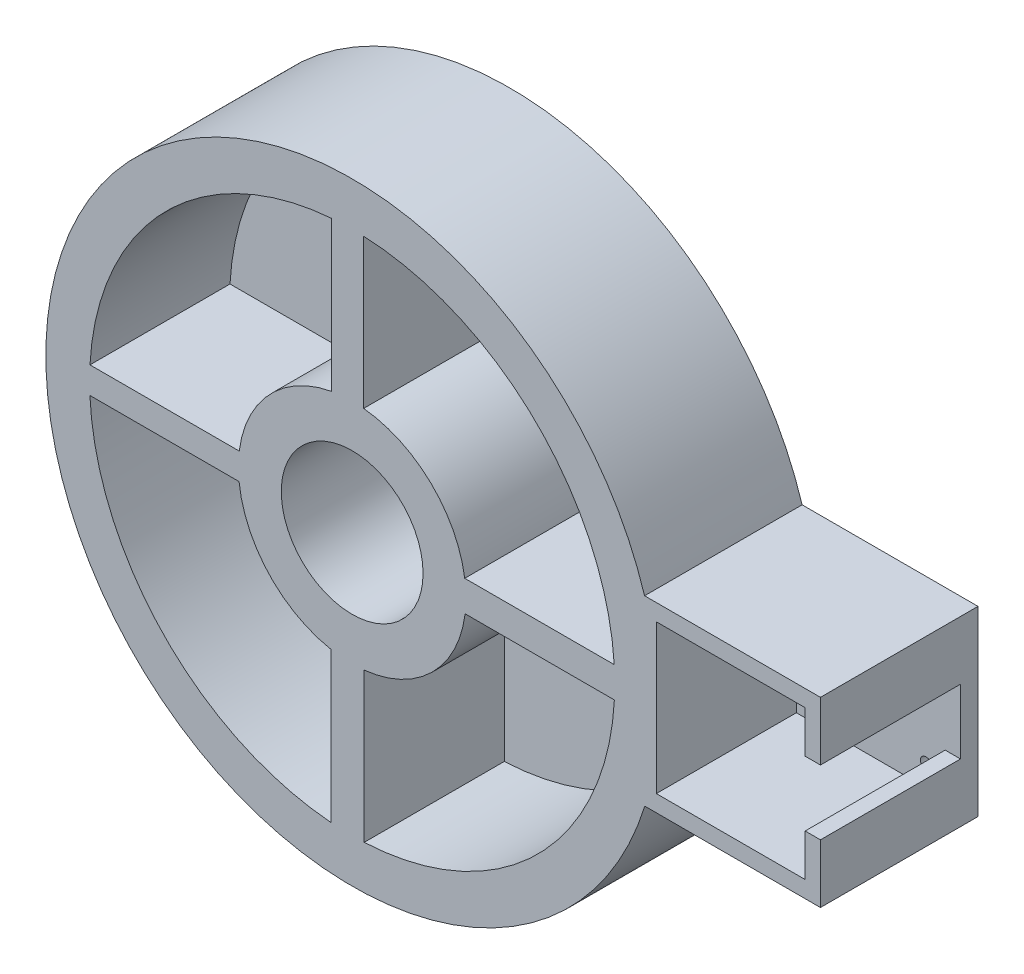
SolidWorks part; units mm, degrees
ref_plane "Front Plane" through (0, 0, 0) normal (1, 0, 0) x (0, 1, 0)
ref_plane "Top Plane" through (0, 0, 0) normal (0, 0, 1) x (0, 1, 0)
ref_plane "Right Plane" through (0, 0, 0) normal (0, 1, 0) x (-1, 0, 0)
sketch "Sketch1" plane through (0, 0, 0) normal (0, 0, 1) x (0, 1, 0)
  line L0 (74.7541, 18.7511) -> (74.7541, -170.9285) construction
  line L5 (-17.0261, -75) -> (164.516, -75) construction
  line L6 (149.5245, -70.2254) -> (106.7208, -70.2254)
  line L7 (149.6823, -79.3694) -> (107.0881, -79.3694)
  line L8 (70.7832, -150.9835) -> (70.7832, -108.3452)
  line L9 (79.4985, -150.9385) -> (79.4985, -108.2405)
  line L10 (-0.0039, -70.0678) -> (42.8166, -70.0678)
  line L11 (-0.1671, -79.527) -> (42.4365, -79.527)
  line L12 (71.2039, -1.1727) -> (71.2039, -43.7831)
  line L13 (78.7713, -1.1963) -> (78.7713, -43.8379)
  line L14 (48.8611, -159.6698) -> (48.8611, -209.836)
  line L15 (53.8611, -163.5887) -> (95.8611, -163.5887)
  line L16 (53.8611, -163.5887) -> (53.8611, -204.836)
  line L17 (53.8611, -204.836) -> (65.8611, -204.836)
  line L18 (95.8611, -163.5887) -> (95.8611, -204.836)
  line L19 (48.8611, -209.836) -> (65.8611, -209.836)
  line L20 (100.8611, -159.6032) -> (100.8611, -209.836)
  line L22 (83.8611, -209.836) -> (100.8611, -209.836)
  line L23 (48.8611, -158.5887) -> (100.8611, -158.5887) construction
  line L24 (48.8611, -158.5887) -> (48.8611, -209.836) construction
  line L25 (100.8611, -158.5887) -> (100.8611, -209.836) construction
  line L26 (65.8611, -204.836) -> (65.8611, -209.836)
  line L27 (83.8611, -204.836) -> (83.8611, -209.836)
  line L28 (83.8611, -204.836) -> (95.8611, -204.836)
  line L30 (53.8611, -204.836) -> (95.8611, -204.836) construction
  line L31 (48.8611, -209.836) -> (100.8611, -209.836) construction
  arc A0 (71.2039, -1.1727) -> (-0.0039, -70.0678) centre (74.7541, -76.0887) ccw
  arc A1 (100.8611, -159.6032) -> (48.8611, -159.6698) centre (74.7541, -76.0887) ccw
  circle A2 centre (74.7541, -76.0887) radius 20
  arc A3 (71.2039, -43.7831) -> (42.8166, -70.0678) centre (74.7541, -76.0887) ccw
  arc A4 (-0.1671, -79.527) -> (70.7832, -150.9835) centre (74.7541, -76.0887) ccw
  circle A5 centre (74.7541, -76.0887) radius 75 construction
  arc A6 (149.5245, -70.2254) -> (78.7713, -1.1963) centre (74.7541, -76.0887) ccw
  arc A7 (79.4985, -150.9385) -> (149.6823, -79.3694) centre (74.7541, -76.0887) ccw
  arc A8 (42.4365, -79.527) -> (70.7832, -108.3452) centre (74.7541, -76.0887) ccw
  circle A9 centre (74.7541, -76.0887) radius 32.5 construction
  arc A10 (79.4985, -108.2405) -> (107.0881, -79.3694) centre (74.7541, -76.0887) ccw
  arc A11 (106.7208, -70.2254) -> (78.7713, -43.8379) centre (74.7541, -76.0887) ccw
  circle A13 centre (74.7541, -76.0887) radius 87.5 construction
  point P3 (146.7229, -53.1149)
  point P13 (107.5, -75.0428)
  point P33 (158.4294, -49.4603)
  dimension "D1" = 150
  dimension "D2" = 40
  dimension "D4" = 12.5
  dimension "D5" = 5
  dimension "D6" = 42
  dimension "D3" = 12.5
extrude "Boss-Extrude4" add sketch "Sketch1" along normal blind 40 contours A2 | A3 L10 A0 L12 | A4 L8 A8 L11 | L6 A11 L13 A6 | A7 L7 A10 L9 | L14 L19 L26 L17 L16 L15 L18 L28 L27 L22 L20 A1
sketch "Sketch4" plane through (0, 0, 0) normal (0, 0, -1) x (1, 0, 0)
  line L0 (159.6698, -48.8611) -> (209.836, -48.8611)
  line L1 (159.6698, -48.8611) -> (209.836, -48.8611) construction
  line L2 (209.836, -48.8611) -> (209.836, -65.8611) construction
  line L3 (209.836, -48.8611) -> (209.836, -100.8611)
  line L4 (209.836, -100.8611) -> (159.6032, -100.8611)
  arc A0 (159.6698, -48.8611) -> (159.6032, -100.8611) centre (76.0887, -74.7541) ccw
extrude "Boss-Extrude5" add sketch "Sketch4" along normal blind 5
sketch "Sketch6" plane through (0, 0, -5) normal (0, 0, -1) x (1, 0, 0)
  circle A0 centre (199.9623, -59.6111) radius 1.25
  circle A1 centre (168.9623, -59.6111) radius 1.25
  circle A2 centre (168.9623, -90.6111) radius 1.25
  circle A3 centre (199.9623, -90.6111) radius 1.25
extrude "Cut-Extrude1" cut sketch "Sketch6" against normal blind 5
sketch "Sketch7" plane through (0, 0, -5) normal (0, 0, -1) x (-1, 0, 0)
  circle A0 centre (-199.9623, 59.6111) radius 3
  circle A1 centre (-168.9623, 59.6111) radius 3
  circle A2 centre (-168.9623, 90.6111) radius 3
  circle A3 centre (-199.9623, 90.6111) radius 3
extrude "Cut-Extrude2" cut sketch "Sketch7" against normal blind 2
sketch "Sketch8" plane through (0, 0, 40) normal (0, 0, 1) x (1, 0, 0)
  circle A0 centre (76.0887, 74.7541) radius 20.25
  dimension "D1" = 40.5
extrude "Cut-Extrude3" cut sketch "Sketch8" against normal blind 40
sketch "Sketch9" plane through (0, 0, 40) normal (0, 0, 1) x (1, 0, 0)
  line L0 (163.5887, 53.8611) -> (204.836, 95.8611) construction
  line L1 (163.5887, 95.8611) -> (204.836, 53.8611) construction
  line L3 (162.9623, 96.1111) -> (205.4623, 96.1111)
  line L4 (162.9623, 96.1111) -> (162.9623, 53.6111)
  line L5 (162.9623, 53.6111) -> (205.4623, 53.6111)
  line L6 (205.4623, 96.1111) -> (205.4623, 53.6111)
  line L7 (162.9623, 96.1111) -> (205.4623, 53.6111) construction
  line L8 (162.9623, 53.6111) -> (205.4623, 96.1111) construction
  point P8 (184.2123, 74.8611)
  dimension "D1" = 42.5
  dimension "D2" = 42.5
extrude "Cut-Extrude4" cut sketch "Sketch9" against normal up to surface (40 mm away) up to face at (198.7123, 90.6111, 0)
sketch "Sketch10" plane through (209.836, 0, 0) normal (1, 0, 0) x (0, 1, 0)
  line L0 (65.8611, 0) -> (83.8611, 40) construction
  line L1 (65.8611, 40) -> (83.8611, 0) construction
  line L3 (65.6111, 40) -> (84.1111, 40)
  line L4 (65.6111, 40) -> (65.6111, 0)
  line L5 (65.6111, 0) -> (84.1111, 0)
  line L6 (84.1111, 40) -> (84.1111, 0)
  line L7 (65.6111, 40) -> (84.1111, 0) construction
  line L8 (65.6111, 0) -> (84.1111, 40) construction
  point P8 (74.8611, 20)
  dimension "D1" = 18.5
  dimension "D2" = 40
extrude "Cut-Extrude5" cut sketch "Sketch10" against normal blind 7
sketch "Sketch11" plane through (0, 0, 0) normal (0, 0, 1) x (1, 0, 0)
  circle A0 centre (168.9623, 90.6111) radius 1.6
  circle A1 centre (199.9623, 90.6111) radius 1.6
  circle A2 centre (168.9623, 59.6111) radius 1.6
  circle A3 centre (199.9623, 59.6111) radius 1.6
  dimension "D1" = 3.2
extrude "Cut-Extrude6" cut sketch "Sketch11" against normal through all
